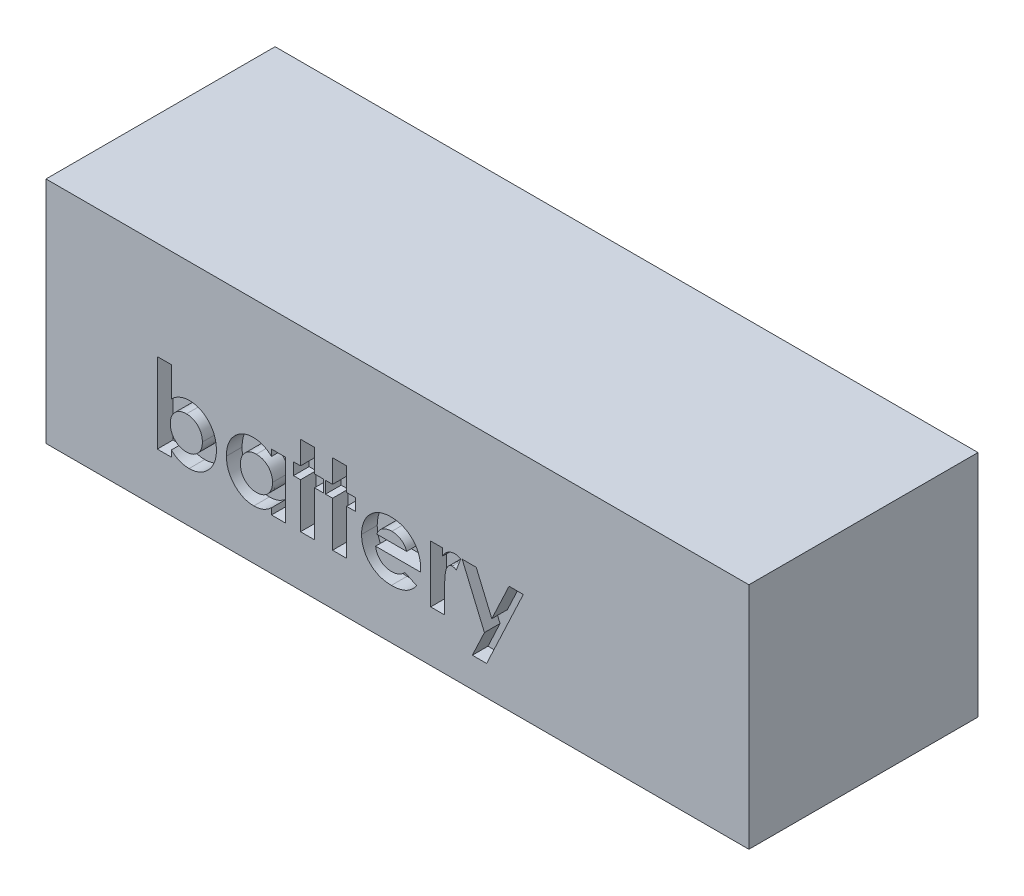
SolidWorks part; units mm, degrees
ref_plane "正面" through (0, 0, 0) normal (0, 0, 1) x (1, 0, 0)
ref_plane "平面" through (0, 0, 0) normal (0, 1, 0) x (1, 0, 0)
ref_plane "右側面" through (0, 0, 0) normal (1, 0, 0) x (0, 0, -1)
sketch "ｽｹｯﾁ1" plane through (0, 0, 0) normal (0, 0, 1) x (1, 0, 0)
  line L1 (0, 0) -> (135, 0)
  line L2 (0, 0) -> (0, 44)
  line L3 (0, 44) -> (135, 44)
  line L4 (135, 0) -> (135, 44)
  dimension "D1" = 135
  dimension "D2" = 44
extrude "ﾎﾞｽ - 押し出し1" add sketch "ｽｹｯﾁ1" along normal blind 44
sketch "ｽｹｯﾁ2" plane through (0, 0, 44) normal (0, 0, 1) x (1, 0, 0)
  text T0 "<b>battery</b>" font "Century Gothic" height 15
extrude "ｶｯﾄ - 押し出し1" cut sketch "ｽｹｯﾁ2" against normal blind 3
